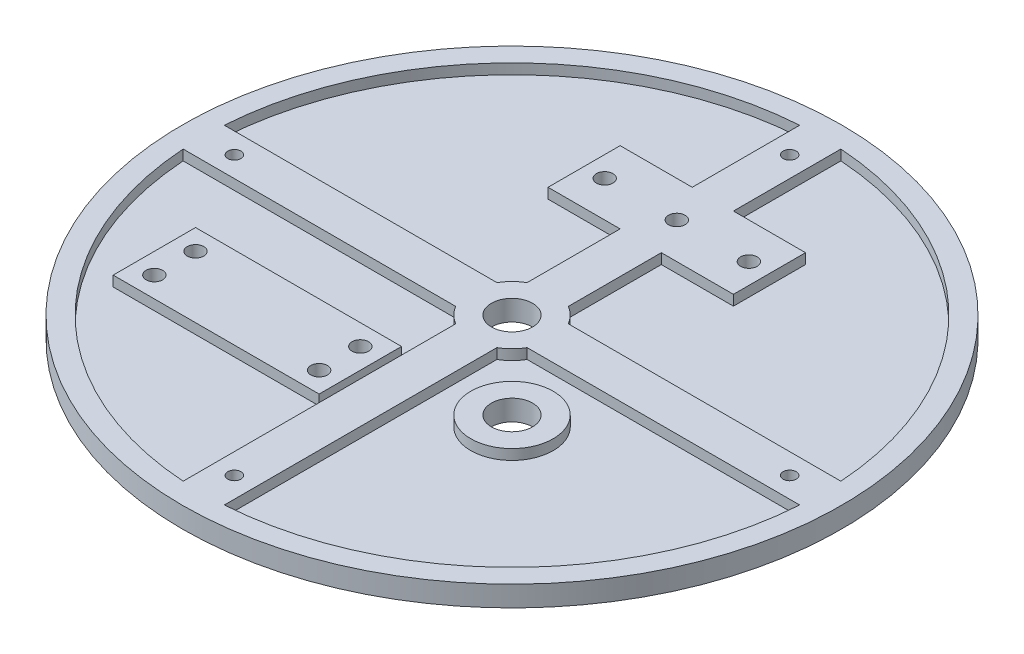
SolidWorks part; units mm, degrees
ref_plane "Front Plane" through (0, 0, 0) normal (0, 0, 1) x (1, 0, 0)
ref_plane "Top Plane" through (0, 0, 0) normal (0, 1, 0) x (1, 0, 0)
ref_plane "Right Plane" through (0, 0, 0) normal (1, 0, 0) x (0, 0, -1)
sketch "Sketch3" plane through (0, 0, 0) normal (0, 1, 0) x (1, 0, 0)
  circle A0 centre (0, 0) radius 101.6
  dimension "D1" = 203.2
extrude "Boss-Extrude1" add sketch "Sketch3" along normal blind 6.35
sketch "Sketch4" plane through (0, 6.35, 0) normal (0, 1, 0) x (1, 0, 0)
  line L0 (0, 0) -> (71.842, -71.842) construction
  line L1 (71.842, -71.842) -> (71.842, 0)
  line L2 (71.842, 0) -> (0, 0)
  line L3 (71.842, -71.842) -> (0, -71.842)
  line L4 (0, -71.842) -> (0, 0)
  line L5 (-85.5998, 0) -> (85.5998, 0) construction
  line L6 (0, 85.5998) -> (0, -85.5998) construction
  line L7 (-85.5998, 0) -> (0, 85.5998)
  line L8 (0, 85.5998) -> (85.5998, 0)
  line L9 (85.5998, 0) -> (0, -85.5998)
  line L10 (0, -85.5998) -> (-85.5998, 0)
  circle A0 centre (0, 0) radius 6.35
  circle A1 centre (0, 0) radius 101.6
  circle A2 centre (26.6624, -26.6624) radius 6.35
  dimension "D1" = 12.7
  dimension "D2" = 203.2
  dimension "D4" = 37.7063
  dimension "D5" = 12.7
  dimension "D3" = 71.842
  dimension "D6" = 171.1996
  dimension "D7" = 171.1996
extrude "Cut-Extrude1" cut sketch "Sketch4" against normal through all contours L2 A0 L4 | L4 A0 L2 | A2
hole_wizard "#10-32 Tapped Hole1" positions "3DSketch1" profile "Sketch5" tap size "#10-32" standard "ANSI Inch"
sketch3d "3DSketch1"
  point P0 (0, 6.35, -85.5998)
  point P3 (-85.5998, 6.35, 0)
  point P6 (0, 6.35, 85.5998)
  point P9 (85.5998, 6.35, 0)
sketch "Sketch5" plane through (0, 6.35, -85.5998) normal (1, 0, 0) x (0, 0, 1)
  line L0 (0, 0) -> (0, 14.9293)
  line L1 (0, 14.9293) -> (2.0193, 13.716)
  line L2 (2.0193, 13.716) -> (2.0193, 0)
  line L5 (2.0193, 0) -> (0, 0)
  line L10 (0, 14.9293) -> (-2.0193, 13.716) construction
  line L11 (0, -6.35) -> (0, 107.95) construction
  dimension "Tap Drill Dia." = 4.0386
  dimension "Tap Drill Depth" = 13.716
  dimension "Drill Angle" = 118
cosmetic thread "Hole Thread1" parameters "D1"=6.35, "D2"=4.826
cosmetic thread "Hole Thread2" parameters "D1"=6.35, "D2"=4.826
cosmetic thread "Hole Thread3" parameters "D1"=6.35, "D2"=4.826
cosmetic thread "Hole Thread4" parameters "D1"=6.35, "D2"=4.826
sketch "Sketch6" plane through (0, 6.35, 0) normal (0, 1, 0) x (1, 0, 0)
  line L0 (-9.525, 50.8) -> (9.525, 50.8) construction
  line L1 (-15.875, 61.9125) -> (-9.525, 61.9125)
  line L2 (-15.875, 61.9125) -> (-15.875, 39.6875)
  line L3 (-15.875, 39.6875) -> (-9.525, 39.6875)
  line L4 (-9.525, 61.9125) -> (-9.525, 39.6875)
  line L5 (9.525, 61.9125) -> (15.875, 61.9125)
  line L6 (9.525, 61.9125) -> (9.525, 39.6875)
  line L7 (9.525, 39.6875) -> (15.875, 39.6875)
  line L8 (15.875, 61.9125) -> (15.875, 39.6875)
  line L9 (-27.7114, -25.4) -> (-21.3614, -25.4)
  line L10 (-59.4614, -25.4) -> (-53.1114, -25.4)
  line L11 (-59.4614, -25.4) -> (-59.4614, -50.8)
  line L12 (-59.4614, -50.8) -> (-53.1114, -50.8)
  line L13 (-53.1114, -25.4) -> (-53.1114, -50.8)
  line L14 (-27.7114, -25.4) -> (-27.7114, -50.8)
  line L15 (-27.7114, -50.8) -> (-21.3614, -50.8)
  line L16 (-21.3614, -25.4) -> (-21.3614, -50.8)
  line L17 (-53.1114, -38.1) -> (-27.7114, -38.1) construction
  line L18 (0, 101.6) -> (0, -101.6) construction
  line L19 (-101.6, 0) -> (101.6, 0) construction
  line L20 (6.35, 0) -> (6.35, -101.4014)
  line L21 (-6.35, 0) -> (-6.35, -101.4014)
  line L22 (-6.35, 0) -> (-6.35, 101.4014)
  line L23 (6.35, 0) -> (6.35, 101.4014)
  line L24 (0, 6.35) -> (101.4014, 6.35)
  line L25 (0, -6.35) -> (101.4014, -6.35)
  line L26 (0, 6.35) -> (-101.4014, 6.35)
  line L27 (0, -6.35) -> (-101.4014, -6.35)
  line L28 (-15.875, 50.8) -> (-28.575, 50.8) construction
  line L29 (-28.575, 61.9125) -> (28.575, 61.9125)
  line L30 (-28.575, 61.9125) -> (-28.575, 39.6875)
  line L31 (-28.575, 39.6875) -> (28.575, 39.6875)
  line L32 (28.575, 61.9125) -> (28.575, 39.6875)
  line L33 (-72.1614, -25.4) -> (-21.3614, -25.4)
  line L34 (-72.1614, -25.4) -> (-72.1614, -50.8)
  line L35 (-72.1614, -50.8) -> (-21.3614, -50.8)
  line L37 (15.875, 50.8) -> (28.575, 50.8) construction
  line L38 (-59.4614, -50.8) -> (-21.3614, -50.8)
  line L39 (-21.3614, -25.4) -> (-8.6614, -25.4)
  line L40 (-21.3614, -25.4) -> (-21.3614, -50.8)
  line L41 (-21.3614, -50.8) -> (-8.6614, -50.8)
  line L42 (-8.6614, -25.4) -> (-8.6614, -50.8)
  circle A0 centre (26.6624, -26.6624) radius 12.7
  circle A1 centre (0, 0) radius 95.25
  circle A2 centre (0, 0) radius 101.6 construction
  circle A3 centre (85.5998, 0) radius 6.35
  circle A4 centre (0, -85.5998) radius 6.35
  circle A5 centre (-85.5998, 0) radius 6.35
  circle A6 centre (0, 85.5998) radius 6.35
  circle A7 centre (0, 0) radius 12.7
  circle A8 centre (0, 0) radius 6.35 construction
  circle A9 centre (-22.225, 50.8) radius 6.35
  circle A10 centre (22.225, 50.8) radius 6.35
  point P18 (0, 50.8)
  point P22 (-40.4114, -38.1)
  dimension "D12" = 6.35
  dimension "D13" = 12.7
  dimension "D14" = 12.7
  dimension "D15" = 12.7
  dimension "D16" = 12.7
  dimension "D17" = 25.4
  dimension "D18" = 25.4
  dimension "D28" = 12.7
  dimension "D29" = 12.7
  dimension "D1" = 19.05
  dimension "D2" = 22.225
  dimension "D3" = 6.35
  dimension "D4" = 6.35
  dimension "D5" = 40.4114
  dimension "D6" = 38.1
  dimension "D7" = 25.4
  dimension "D8" = 6.35
  dimension "D9" = 6.35
  dimension "D10" = 25.4
  dimension "D11" = 88.9
  dimension "D19" = 12.7
  dimension "D20" = 12.7
  dimension "D22" = 12.7
  dimension "D23" = 12.7
  dimension "D27" = 12.7
extrude "Cut-Extrude2" cut sketch "Sketch6" against normal blind 3.175 contours A7 L22 L31 L30 L29 A1 L26 | A7 L24 A1 L23 L29 L32 L31 | A7 L20 A1 L25 A0 | A7 L27 A1 L21 L33 L41 L35 L34
hole_wizard "1/4-20 Tapped Hole2" positions "3DSketch3" profile "Sketch9" tap size "1/4-20" standard "ANSI Inch"
sketch3d "3DSketch3"
  point P0 (-22.225, 6.35, -50.8)
  point P3 (22.225, 6.35, -50.8)
  point P6 (0, 6.35, -50.8)
sketch "Sketch9" plane through (-22.225, 6.35, -50.8) normal (1, 0, 0) x (0, 0, 1)
  line L0 (0, 0) -> (0, 20.5838)
  line L1 (0, 20.5838) -> (2.5527, 19.05)
  line L2 (2.5527, 19.05) -> (2.5527, 0)
  line L5 (2.5527, 0) -> (0, 0)
  line L10 (0, 20.5838) -> (-2.5527, 19.05) construction
  line L11 (0, -6.35) -> (0, 107.95) construction
  dimension "Tap Drill Dia." = 5.1054
  dimension "Tap Drill Depth" = 19.05
  dimension "Drill Angle" = 118
cosmetic thread "Hole Thread7" parameters "D1"=6.35, "D2"=6.35
cosmetic thread "Hole Thread8" parameters "D1"=6.35, "D2"=6.35
cosmetic thread "Hole Thread9" parameters "D1"=6.35, "D2"=6.35
hole_wizard "1/4-20 Tapped Hole4" positions "3DSketch6" profile "Sketch12" tap size "1/4-20" standard "ANSI Inch"
sketch3d "3DSketch6"
  line L0 (-72.1614, 6.35, 25.4) -> (-72.1614, 6.35, 50.8) construction
  line L1 (-72.1614, 6.35, 25.4) -> (-8.6614, 6.35, 25.4) construction
  line L2 (-72.1614, 6.35, 50.8) -> (-8.6614, 6.35, 50.8) construction
  line L3 (-8.6614, 6.35, 25.4) -> (-8.6614, 6.35, 50.8) construction
  point P0 (-65.8114, 6.35, 31.75)
  point P2 (-65.8114, 6.35, 44.45)
  point P4 (-15.0114, 6.35, 44.45)
  point P6 (-15.0114, 6.35, 31.75)
  dimension "D1" = 6.35
  dimension "D2" = 6.35
  dimension "D3" = 6.35
  dimension "D4" = 6.35
  dimension "D5" = 6.35
  dimension "D6" = 6.35
  dimension "D7" = 6.35
  dimension "D8" = 6.35
sketch "Sketch12" plane through (-65.8114, 6.35, 31.75) normal (1, 0, 0) x (0, 0, 1)
  line L0 (0, 0) -> (0, 20.5838)
  line L1 (0, 20.5838) -> (2.5527, 19.05)
  line L2 (2.5527, 19.05) -> (2.5527, 0)
  line L5 (2.5527, 0) -> (0, 0)
  line L10 (0, 20.5838) -> (-2.5527, 19.05) construction
  line L11 (0, -6.35) -> (0, 107.95) construction
  dimension "Tap Drill Dia." = 5.1054
  dimension "Tap Drill Depth" = 19.05
  dimension "Drill Angle" = 118
cosmetic thread "Hole Thread14"
cosmetic thread "Hole Thread15"
cosmetic thread "Hole Thread16"
cosmetic thread "Hole Thread17"
